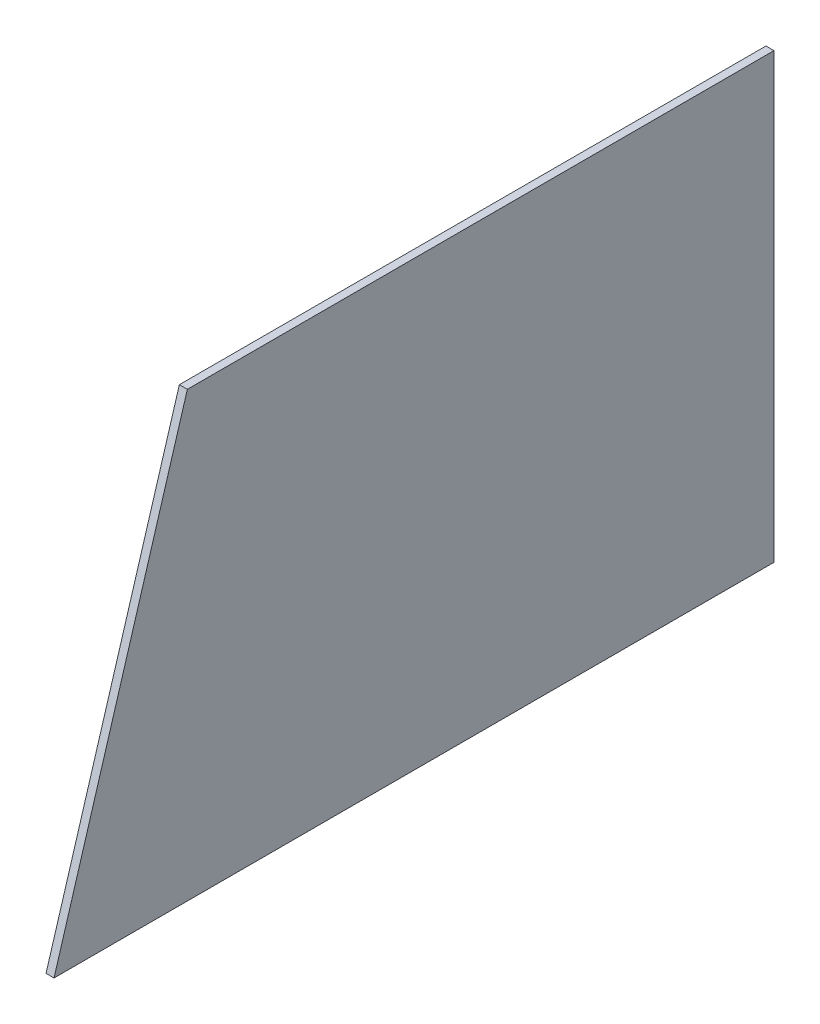
SolidWorks part; units mm, degrees
ref_plane "Front Plane" through (0, 0, 0) normal (0, 0, 1) x (1, 0, 0)
ref_plane "Top Plane" through (0, 0, 0) normal (0, 1, 0) x (1, 0, 0)
ref_plane "Right Plane" through (0, 0, 0) normal (1, 0, 0) x (0, 0, -1)
sketch "Sketch1" plane through (0, 0, 0) normal (1, 0, 0) x (0, 0, -1)
  line L0 (-220, 67.4721) -> (0, 67.4721)
  line L1 (0, 67.4721) -> (0, -98.7356)
  line L2 (0, -98.7356) -> (-270, -98.7356)
  line L3 (-270, -98.7356) -> (-220, 67.4721)
extrude "Boss-Extrude1" add sketch "Sketch1" along normal blind 3
